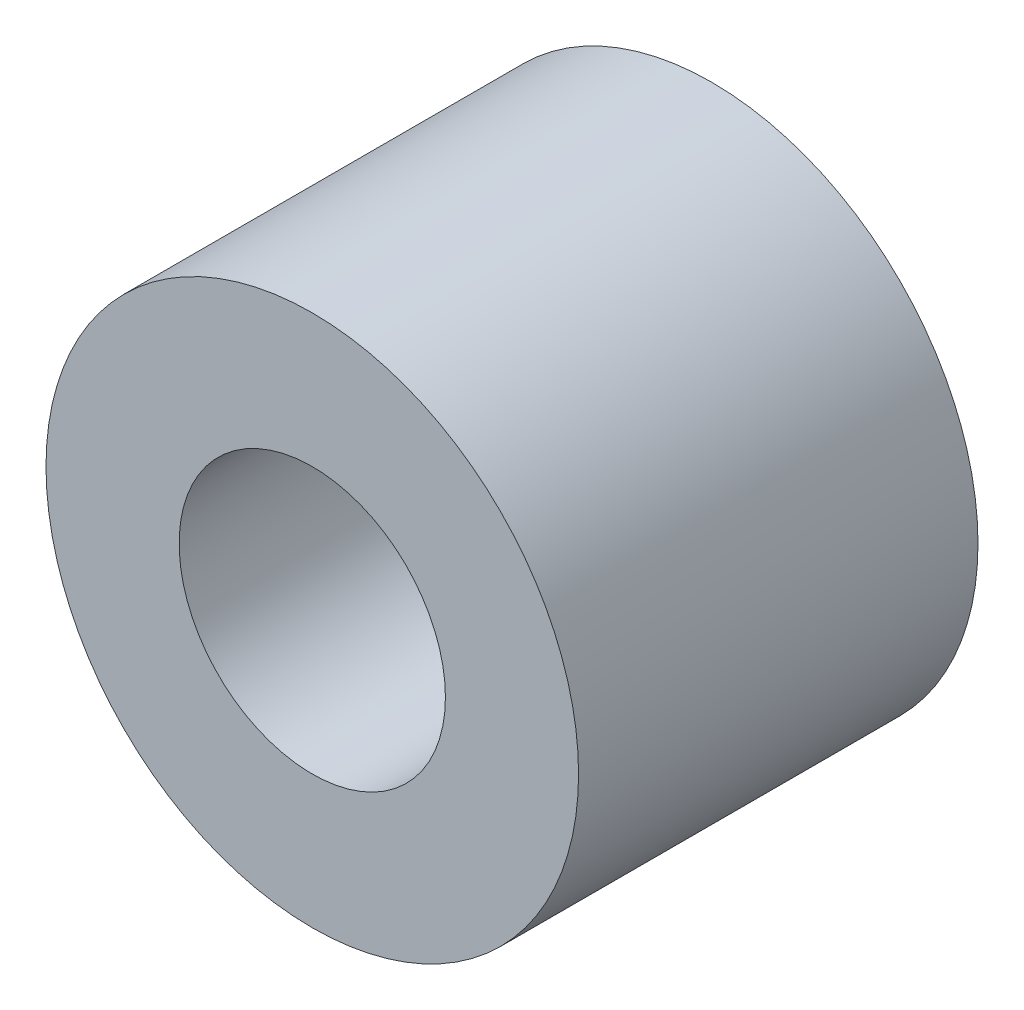
SolidWorks part; units mm, degrees
material "AISI 304"
ref_plane "前视基准面" through (0, 0, 0) normal (0, 0, 1) x (1, 0, 0)
ref_plane "上视基准面" through (0, 0, 0) normal (0, 1, 0) x (1, 0, 0)
ref_plane "右视基准面" through (0, 0, 0) normal (1, 0, 0) x (0, 0, -1)
other "Configuration Table"
sketch "草图1" plane through (0, 0, 0) normal (0, 0, 1) x (1, 0, 0)
  line L0 (-5.037, 0) -> (4.0741, 0) construction
  line L1 (0, 2.9259) -> (0, -3.9259) construction
  circle A0 centre (0, 0) radius 2
  circle A1 centre (0, 0) radius 4
  dimension "D1" = 4
  dimension "D2" = 8
extrude "凸台-拉伸1" add sketch "草图1" along normal mid plane 6
